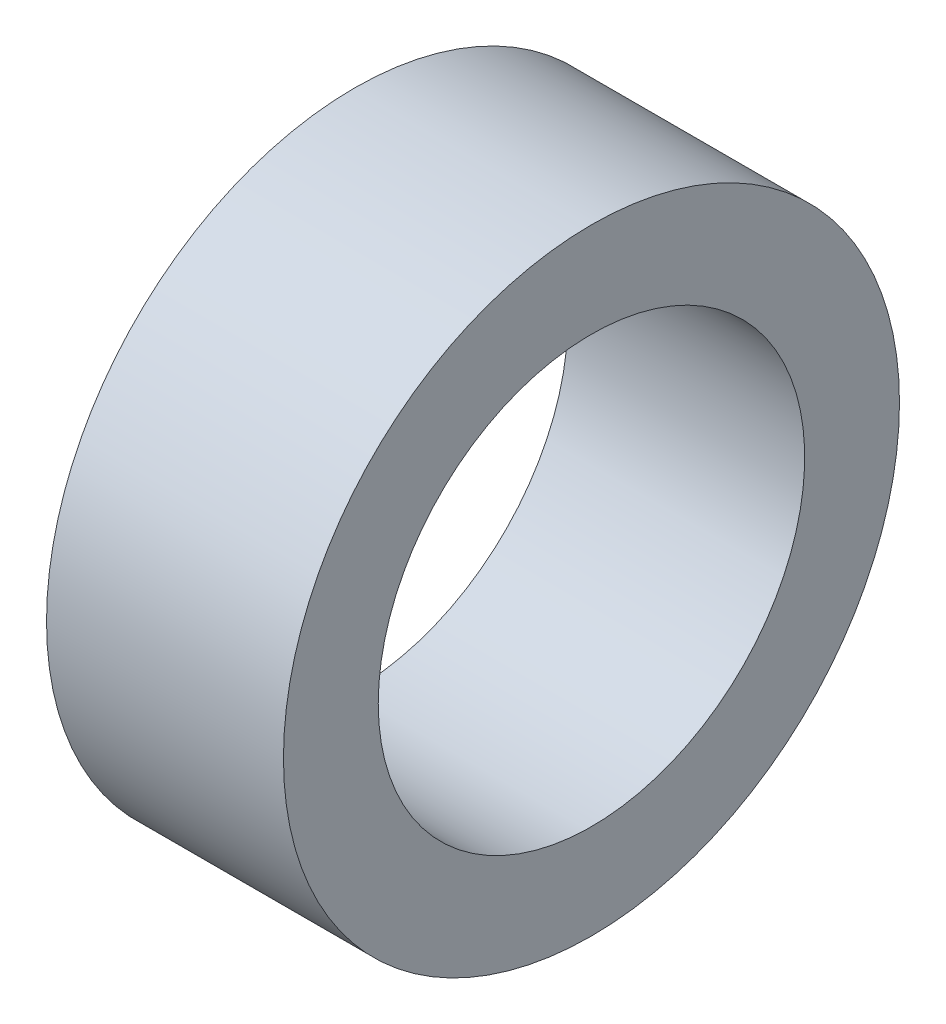
SolidWorks part; units mm, degrees
ref_plane "前视基准面" through (0, 0, 0) normal (0, 0, 1) x (1, 0, 0)
ref_plane "上视基准面" through (0, 0, 0) normal (0, 1, 0) x (1, 0, 0)
ref_plane "右视基准面" through (0, 0, 0) normal (1, 0, 0) x (0, 0, -1)
other "Configuration Table"
sketch "草图1" plane through (0, 0, 0) normal (0, 0, 1) x (1, 0, 0)
  line L0 (-5, 0) -> (15, 0) construction
  line L1 (0, 9) -> (0, 13)
  line L2 (0, 13) -> (10, 13)
  line L3 (10, 13) -> (10, 9)
  line L4 (10, 9) -> (0, 9)
revolve "01_PACKING" add sketch "草图1" angle 360 about L0
